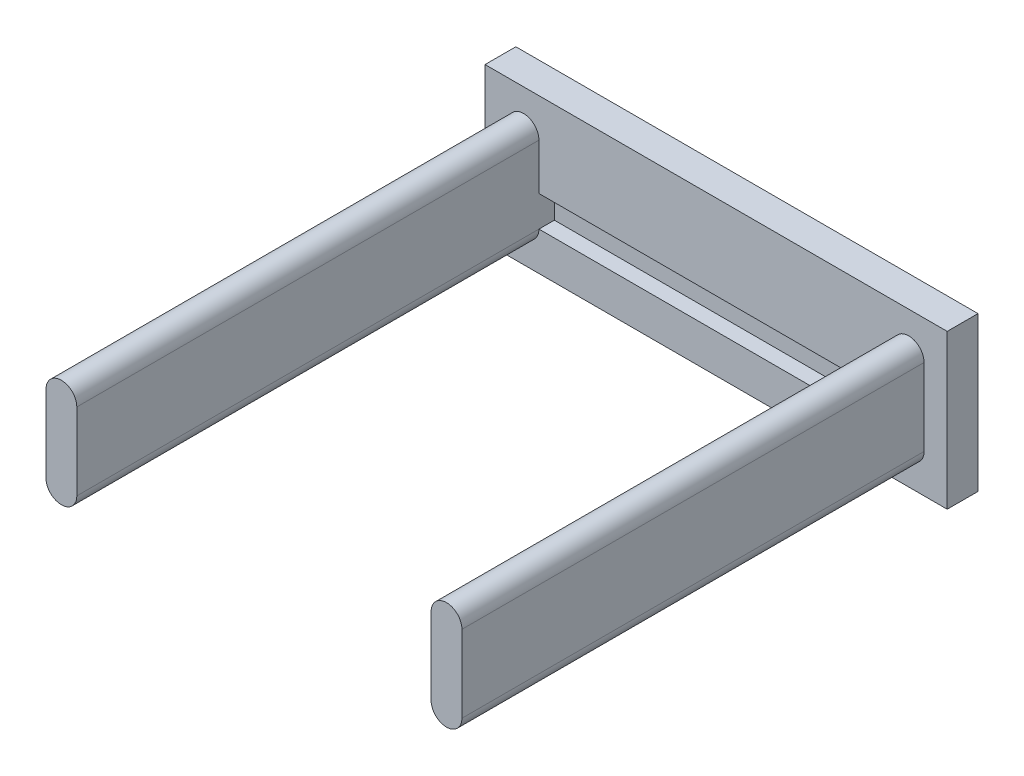
SolidWorks part; units mm, degrees
ref_plane "Alzado" through (0, 0, 0) normal (0, 0, 1) x (1, 0, 0)
ref_plane "Planta" through (0, 0, 0) normal (0, 1, 0) x (1, 0, 0)
ref_plane "Vista lateral" through (0, 0, 0) normal (1, 0, 0) x (0, 0, -1)
sketch "Croquis1" plane through (0, 0, 0) normal (0, 0, 1) x (1, 0, 0)
  line L1 (-15, 5) -> (15, 5)
  line L2 (-15, 5) -> (-15, -5)
  line L3 (-15, -5) -> (15, -5)
  line L4 (15, 5) -> (15, -5)
  line L5 (-15, 5) -> (15, -5) construction
  line L6 (-15, -5) -> (15, 5) construction
  point P0 (0, 0)
  dimension "D1" = 30
  dimension "D2" = 10
extrude "Saliente-Extruir1" add sketch "Croquis1" along normal blind 2
sketch "Croquis2" plane through (0, 0, 2) normal (0, 0, 1) x (1, 0, 0)
  line L0 (-11.5, 0) -> (11.5, 0)
  line L2 (11.5, 2.5) -> (11.5, -2.5)
  line L3 (13.5, 2.5) -> (13.5, -2.5)
  line L4 (-11.5, -2.5) -> (-11.5, 2.5)
  line L5 (-13.5, -2.5) -> (-13.5, 2.5)
  arc A1 (-11.5, 2.5) -> (-13.5, 2.5) centre (-12.5, 2.5) ccw
  arc A2 (-13.5, -2.5) -> (-11.5, -2.5) centre (-12.5, -2.5) ccw
  arc A3 (13.5, 2.5) -> (11.5, 2.5) centre (12.5, 2.5) ccw
  arc A4 (11.5, -2.5) -> (13.5, -2.5) centre (12.5, -2.5) ccw
  point P4 (0, 0)
  point P10 (-12.5, 0)
  dimension "D3" = 5
extrude "Saliente-Extruir2" add sketch "Croquis2" along normal blind 20 contours L5 A2 L4 A1 | L2 A4 L3 A3
sketch "Croquis3" plane through (0, 0, 2) normal (0, 0, 1) x (1, 0, 0)
  line L0 (-11.5, -2.5) -> (11.5, -2.5)
  line L1 (11.5, -2.5) -> (11.5, -0.5)
  line L2 (11.5, -0.5) -> (-11.5, -0.5)
  line L3 (-11.5, -2.5) -> (-11.5, 2.5) construction
  line L4 (-11.5, -0.5) -> (-11.5, -2.5)
  dimension "D1" = 2
extrude "Cortar-Extruir1" cut sketch "Croquis3" against normal blind 1
sketch "Croquis4" plane through (0, 0, 22) normal (0, 0, 1) x (1, 0, 0)
  line L1 (11.5, 2.5) -> (13.5, 2.5)
  line L2 (11.5, 2.5) -> (11.5, -2.5)
  line L3 (11.5, -2.5) -> (13.5, -2.5)
  line L4 (13.5, 2.5) -> (13.5, -2.5)
  line L5 (-13.5, 2.5) -> (-11.5, 2.5)
  line L6 (-13.5, 2.5) -> (-13.5, -2.5)
  line L7 (-13.5, -2.5) -> (-11.5, -2.5)
  line L8 (-11.5, 2.5) -> (-11.5, -2.5)
  circle A0 centre (-12.5, 2.5) radius 1
  circle A1 centre (-12.5, -2.5) radius 1
  circle A2 centre (12.5, -2.5) radius 1
  circle A3 centre (12.5, 2.5) radius 1
  line M1 (-13.5, 2.5) -> (-13.5, -2.5)
  arc M2 (-13.5, -2.5) -> (-11.5, -2.5) centre (-12.5, -2.5) ccw
  line M3 (-11.5, -2.5) -> (-11.5, 2.5)
  arc M4 (-11.5, 2.5) -> (-13.5, 2.5) centre (-12.5, 2.5) ccw
extrude "Saliente-Extruir3" add sketch "Croquis4" along normal blind 10 contours L5 M4 | L5 A0 | A1 A0 M3 M1 | L7 M2 | L7 A1 | L3 A2 | L3 A2 | A3 L2 A2 L4 | L1 A3 | L1 A3
